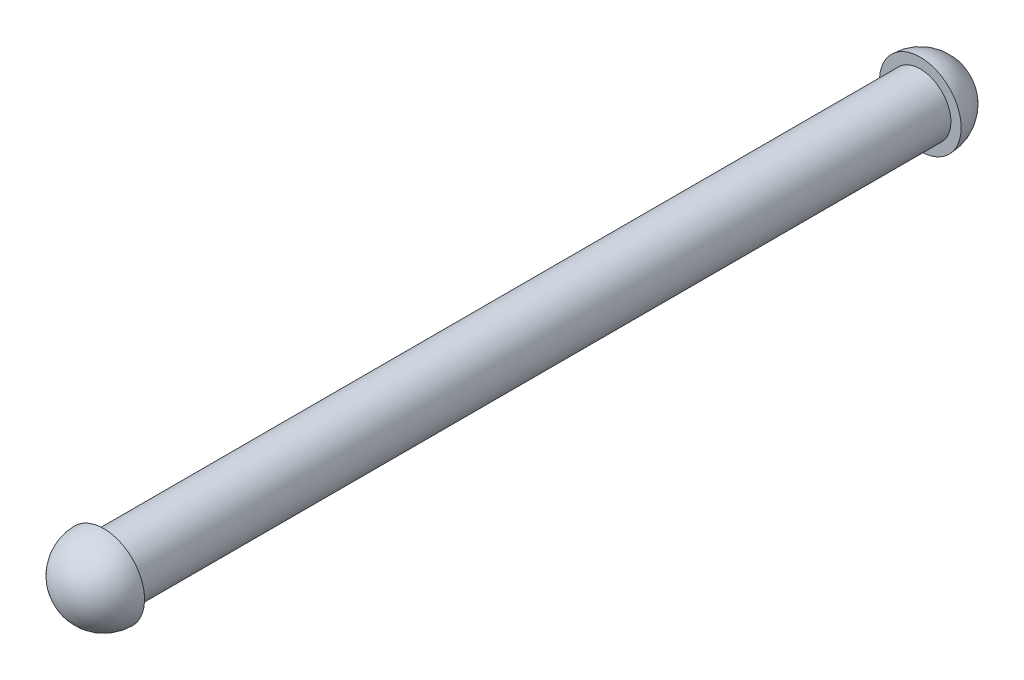
SolidWorks part; units mm, degrees
material "AISI 304"
ref_plane "前视基准面" through (0, 0, 0) normal (0, 0, 1) x (1, 0, 0)
ref_plane "上视基准面" through (0, 0, 0) normal (0, 1, 0) x (1, 0, 0)
ref_plane "右视基准面" through (0, 0, 0) normal (1, 0, 0) x (0, 0, -1)
sketch "草图1" plane through (0, 0, 0) normal (0, 0, 1) x (1, 0, 0)
  line L0 (-0.5, 0) -> (0.5, 0)
  arc A0 (-0.5, 0) -> (0.5, 0) centre (0, 0) ccw
  dimension "D1" = 1
revolve "旋转1" add sketch "草图1" angle 180 about L0
sketch "草图2" plane through (0, 0, 0) normal (0, 0, 1) x (1, 0, 0)
  circle A0 centre (0, 0) radius 0.375
  dimension "D1" = 0.75
extrude "凸台-拉伸1" add sketch "草图2" along normal blind 10
sketch "草图3" plane through (0, 0, 10) normal (0, 0, 1) x (1, 0, 0)
  line L0 (0, 0.5) -> (0, -0.5)
  arc A0 (0, 0.5) -> (0, -0.5) centre (0, 0) ccw
  dimension "D1" = 1
revolve "旋转2" add sketch "草图3" angle 180 about L0
